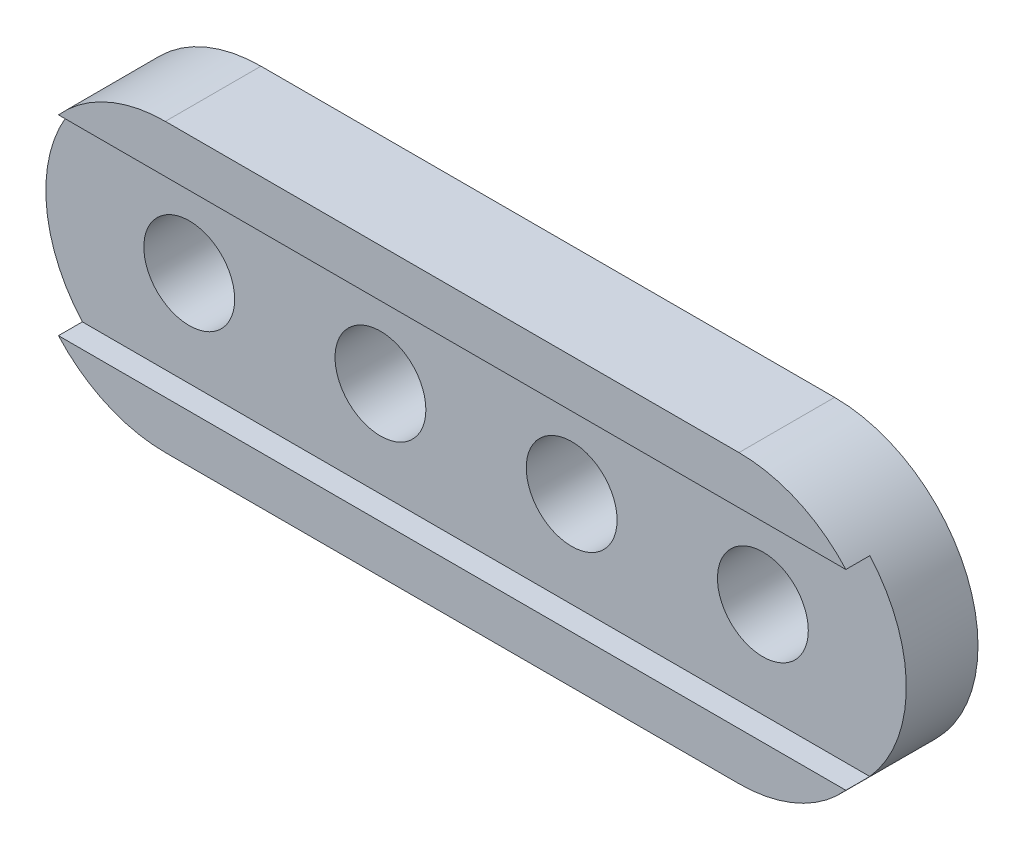
SolidWorks part; units mm, degrees
ref_plane "前视基准面" through (0, 0, 0) normal (0, 0, 1) x (1, 0, 0)
ref_plane "上视基准面" through (0, 0, 0) normal (0, 1, 0) x (1, 0, 0)
ref_plane "右视基准面" through (0, 0, 0) normal (1, 0, 0) x (0, 0, -1)
sketch "草图1" plane through (0, 0, 0) normal (0, 0, 1) x (1, 0, 0)
  line L0 (-12, 0) -> (12, 0) construction
  line L1 (-12, 6) -> (12, 6)
  line L2 (-12, -6) -> (12, -6)
  arc A0 (-12, 6) -> (-12, -6) centre (-12, 0) ccw
  arc A1 (12, -6) -> (12, 6) centre (12, 0) ccw
  point P3 (0, 0)
  dimension "D2" = 6
  dimension "D1" = 24
extrude "凸台-拉伸1" add sketch "草图1" along normal blind 4
sketch "草图2" plane through (0, 0, 4) normal (0, 0, 1) x (1, 0, 0)
  line L1 (-18, 4) -> (18, 4)
  line L2 (-18, 4) -> (-18, -4)
  line L3 (-18, -4) -> (18, -4)
  line L4 (18, 4) -> (18, -4)
  arc A0 (-12, 6) -> (-12, -6) centre (-12, 0) ccw construction
  arc A1 (12, -6) -> (12, 6) centre (12, 0) ccw construction
  point P10 (18, 0)
  dimension "D1" = 8
extrude "切除-拉伸1" cut sketch "草图2" against normal blind 1
sketch "草图3" plane through (0, 0, 3) normal (0, 0, 1) x (1, 0, 0)
  circle A0 centre (-12, 0) radius 1.9
  arc A1 (-16.4721, 4) -> (-16.4721, -4) centre (-12, 0) ccw construction
  dimension "D1" = 4.1
extrude "切除-拉伸2" cut sketch "草图3" against normal blind 3
pattern_linear "阵列(线性)1" count 5 spacing 8 along (1, 0, 0) of "切除-拉伸2"
